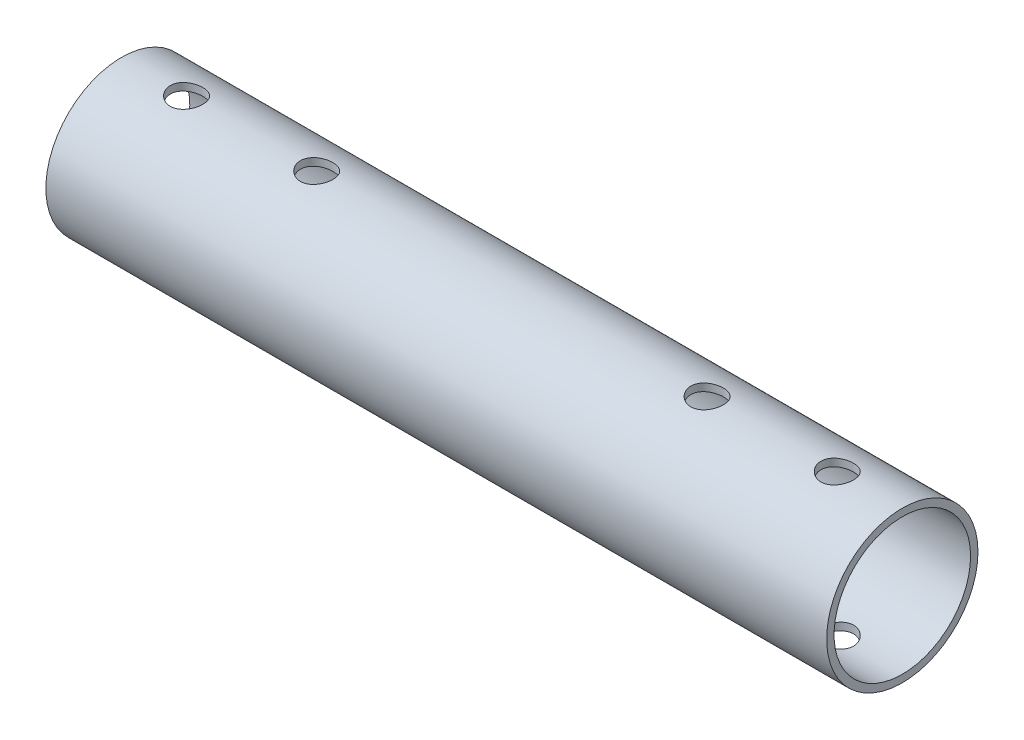
SolidWorks part; units mm, degrees
material "Galvanized Steel"
ref_plane "Front Plane" through (0, 0, 0) normal (0, 0, 1) x (1, 0, 0)
ref_plane "Top Plane" through (0, 0, 0) normal (0, 1, 0) x (1, 0, 0)
ref_plane "Right Plane" through (0, 0, 0) normal (1, 0, 0) x (0, 0, -1)
sketch "Sketch3" plane through (0, 0, 0) normal (1, 0, 0) x (0, 0, -1)
  circle A0 centre (0, 0) radius 13.3223
  circle A1 centre (0, 0) radius 14.7701
  dimension "D1" = 26.6446
  dimension "D2" = 29.5402
extrude "Boss-Extrude1" add sketch "Sketch3" along normal blind 152.4
sketch "Sketch4" plane through (0, 0, 0) normal (0, 1, 0) x (1, 0, 0)
  line L0 (0, 14.7701) -> (0, -14.7701) construction
  line L1 (152.4, -14.7701) -> (152.4, 14.7701) construction
  circle A0 centre (12.7, 0) radius 3.175
  circle A1 centre (38.1, 0) radius 3.175
  circle A2 centre (139.7, 0) radius 3.175
  circle A3 centre (114.3, 0) radius 3.175
  dimension "D1" = 12.7
  dimension "D2" = 38.1
  dimension "D3" = 12.7
  dimension "D4" = 38.1
extrude "Cut-Extrude1" cut sketch "Sketch4" against normal through all and the other way through all
